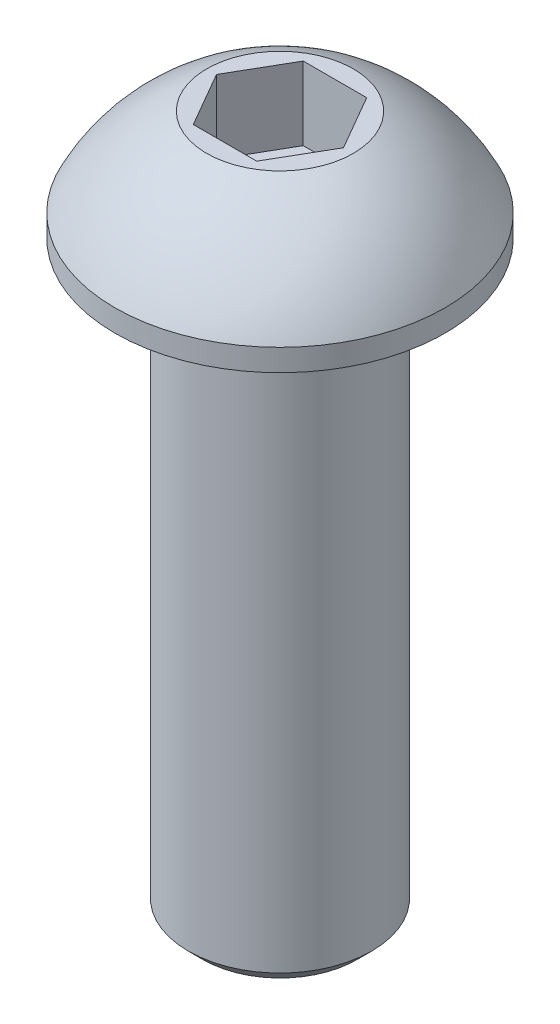
SolidWorks part; units mm, degrees
material "1023 Carbon Steel Sheet (SS)"
ref_plane "Front Plane" through (0, 0, 0) normal (0, 0, 1) x (1, 0, 0)
ref_plane "Top Plane" through (0, 0, 0) normal (0, 1, 0) x (1, 0, 0)
ref_plane "Right Plane" through (0, 0, 0) normal (1, 0, 0) x (0, 0, -1)
sketch "Sketch1" plane through (0, 0, 0) normal (0, 0, 1) x (1, 0, 0)
  line L0 (0, 21.3441) -> (0, -8.2398) construction
  line L1 (1.25, 0) -> (2.25, 0)
  line L2 (1.25, 0) -> (1.25, -8)
  line L3 (1.25, -8) -> (0, -8)
  line L4 (0, -8) -> (0, 1.5)
  line L5 (0, 1.5) -> (1, 1.5)
  line L6 (2.25, 0) -> (2.25, 0.3)
  arc A0 (1, 1.5) -> (2.25, 0.3) centre (0, -0.7927) cw
  dimension "D1" = 4.5
  dimension "D2" = 2.5
  dimension "D3" = 1.5
  dimension "D4" = 2
  dimension "D5" = 0.3
  dimension "D6" = 8
revolve "Revolve1" add sketch "Sketch1" angle 360 about L0
cosmetic thread "Cosmetic Thread1" parameters "D1"=11.8, "D2"=2.439
sketch "Sketch2" plane through (0, 0, 0) normal (0, 1, 0) x (1, 0, 0)
  line L1 (0.433, -0.75) -> (0.866, 0)
  line L2 (0.866, 0) -> (0.433, 0.75)
  line L3 (0.433, 0.75) -> (-0.433, 0.75)
  line L4 (-0.433, 0.75) -> (-0.866, 0)
  line L5 (-0.866, 0) -> (-0.433, -0.75)
  line L6 (-0.433, -0.75) -> (0.433, -0.75)
  circle A0 centre (0, 0) radius 0.75 construction
  dimension "D1" = 1.5
chamfer "Chamfer1" distance 0.2 angle 45 1 edges at (0, -8, 1.25)
extrude "Cut-Extrude1" cut sketch "Sketch2" along normal blind 10 from offset 0.5
fillet "Fillet1" radius 0.2 1 edges at (0, 0, 1.25)
